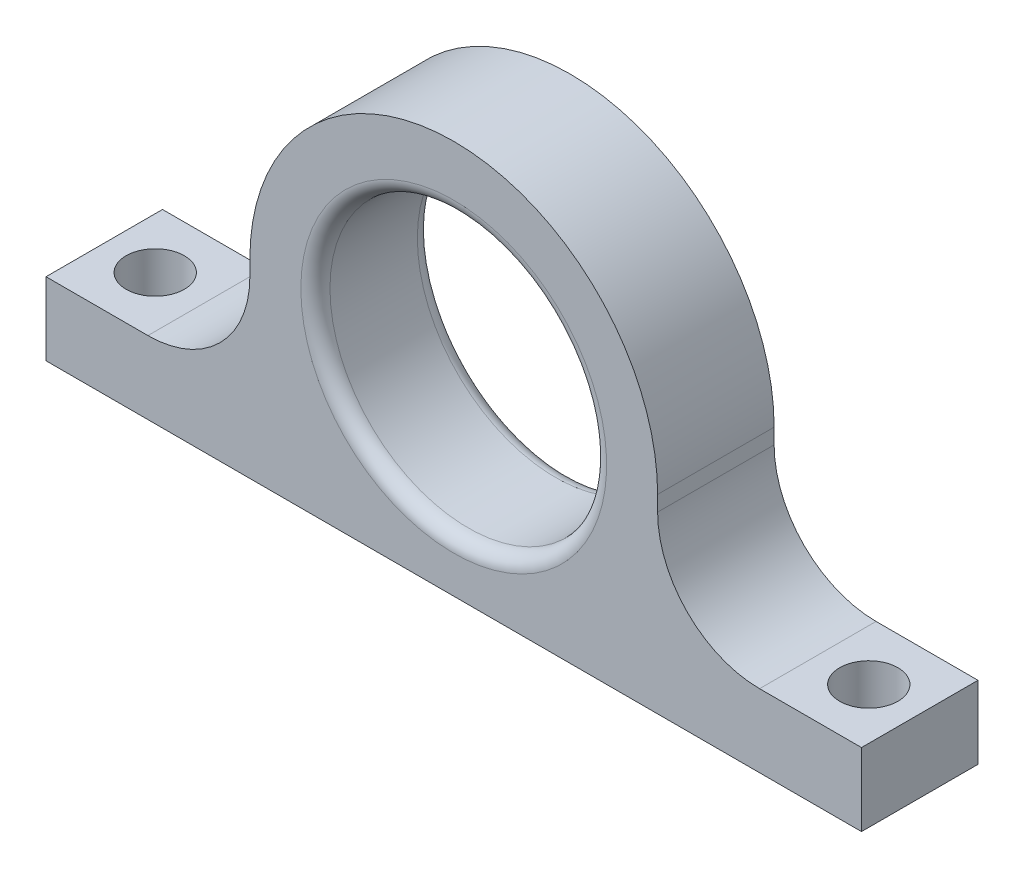
SolidWorks part; units mm, degrees
ref_plane "Plan de face" through (0, 0, 0) normal (0, 0, 1) x (1, 0, 0)
ref_plane "Plan de dessus" through (0, 0, 0) normal (0, 1, 0) x (1, 0, 0)
ref_plane "Plan de droite" through (0, 0, 0) normal (1, 0, 0) x (0, 0, -1)
sketch "Esquisse1" plane through (0, 0, 0) normal (0, 0, 1) x (1, 0, 0)
  line L5 (-12, 11.6293) -> (12, -11.6293) construction
  line L6 (-12, -11.6293) -> (12, 11.6293) construction
  line L9 (0, 0) -> (0, -28.2243) construction
  line L15 (14, -8.0537) -> (28, -8.0537)
  line L17 (14, -8.0537) -> (14, 0)
  line L18 (28, -8.0537) -> (28, -13.0537)
  line L19 (28, -13.0537) -> (-28, -13.0537)
  line L20 (-28, -8.0537) -> (-28, -13.0537)
  line L21 (-14, -8.0537) -> (-28, -8.0537)
  line L22 (-14, -8.0537) -> (-14, 0)
  circle A0 centre (0, 0) radius 9.5
  arc A1 (-14, 0) -> (14, 0) centre (0, 0) cw
  point P6 (0, 0)
  point P14 (0, -13.0537)
  dimension "D1" = 19
  dimension "D3" = 14
  dimension "D2" = 24
  dimension "D4" = 5
  dimension "D5" = 14
extrude "Boss.-Extru.1" add sketch "Esquisse1" along normal blind 8
fillet "Congé1" radius 1 1 edges at (9.5, 0, 8)
fillet "Congé2" radius 1 1 edges at (9.5, 0, 0)
fillet "Congé3" radius 7 2 edges at (14, -8.0537, 4) (-14, -8.0537, 4)
sketch "Esquisse2" plane through (0, -8.0537, 0) normal (0, 1, 0) x (1, 0, 0)
  line L0 (0, 0) -> (0, -16.585) construction
  line L1 (28, 0) -> (21, -8) construction
  circle A0 centre (24.5, -4) radius 2
  circle A1 centre (-24.5, -4) radius 2
  dimension "D1" = 4
extrude "Enlèv. mat.-Extru.1" cut sketch "Esquisse2" against normal blind 6
